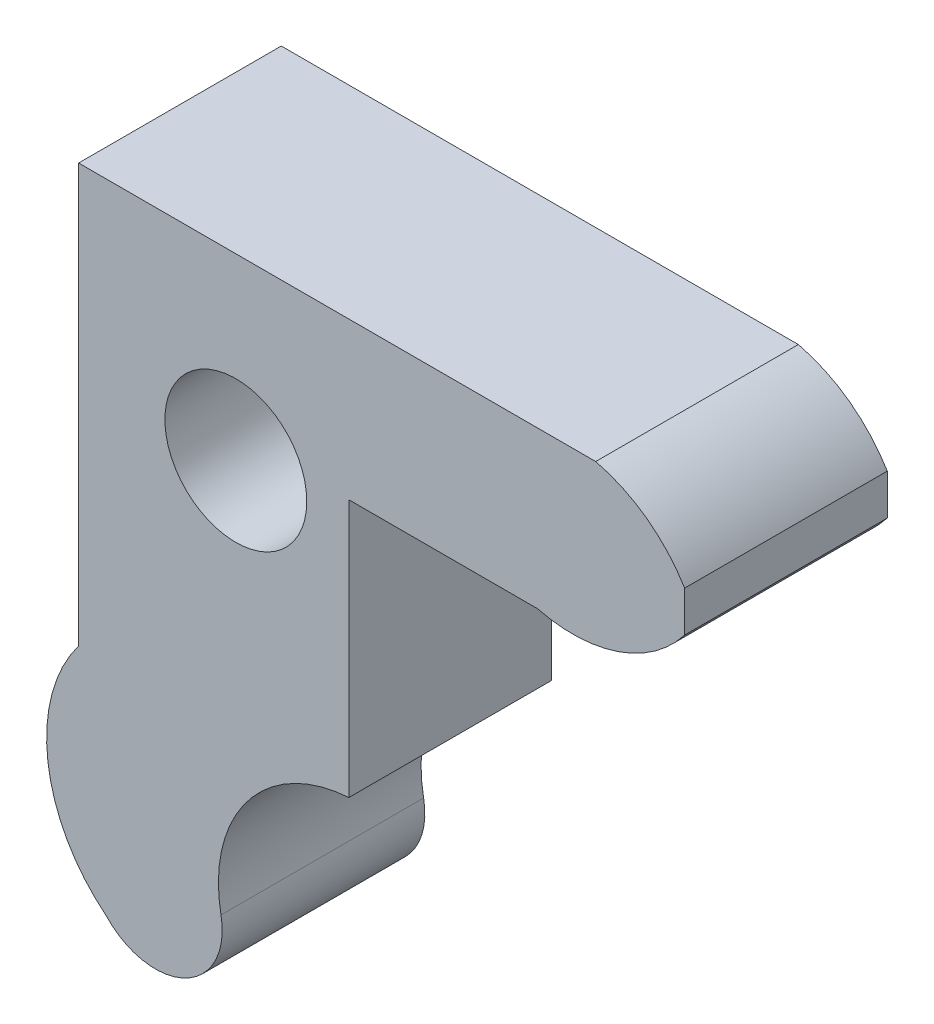
SolidWorks part; units mm, degrees
ref_plane "정면" through (0, 0, 0) normal (0, 0, 1) x (1, 0, 0)
ref_plane "윗면" through (0, 0, 0) normal (0, 1, 0) x (1, 0, 0)
ref_plane "우측면" through (0, 0, 0) normal (1, 0, 0) x (0, 0, -1)
sketch "스케치1" plane through (0, 0, 0) normal (0, 0, 1) x (1, 0, 0)
  line L0 (-4.6547, -7.0798) -> (-4.6547, 5.3018)
  line L1 (-4.6547, 5.3018) -> (10.6551, 5.3018)
  line L2 (13.2887, 3.3727) -> (13.2887, 2.1689)
  line L3 (8.9279, 0.6672) -> (3.3453, 0.6672)
  line L4 (3.3453, 0.6672) -> (3.3453, -6.9688)
  circle A0 centre (0, 0) radius 2.1
  arc A1 (10.6551, 5.3018) -> (13.2887, 3.3727) centre (9.6556, 1.1748) cw
  arc A2 (-4.6547, -7.0798) -> (-3.83, -13.5979) centre (-0.8855, -9.9142) ccw
  arc A3 (-3.83, -13.5979) -> (-0.4398, -11.873) centre (-2.3811, -12.2516) ccw
  arc A4 (-0.4398, -11.873) -> (3.3453, -6.9688) centre (3.6075, -11.0839) cw
  arc A5 (8.9279, 0.6672) -> (13.2887, 2.1689) centre (9.9694, 4.7254) ccw
  dimension "D1" = 4.2
  dimension "D2" = 8
extrude "보스-돌출1" add sketch "스케치1" along normal mid plane 6
